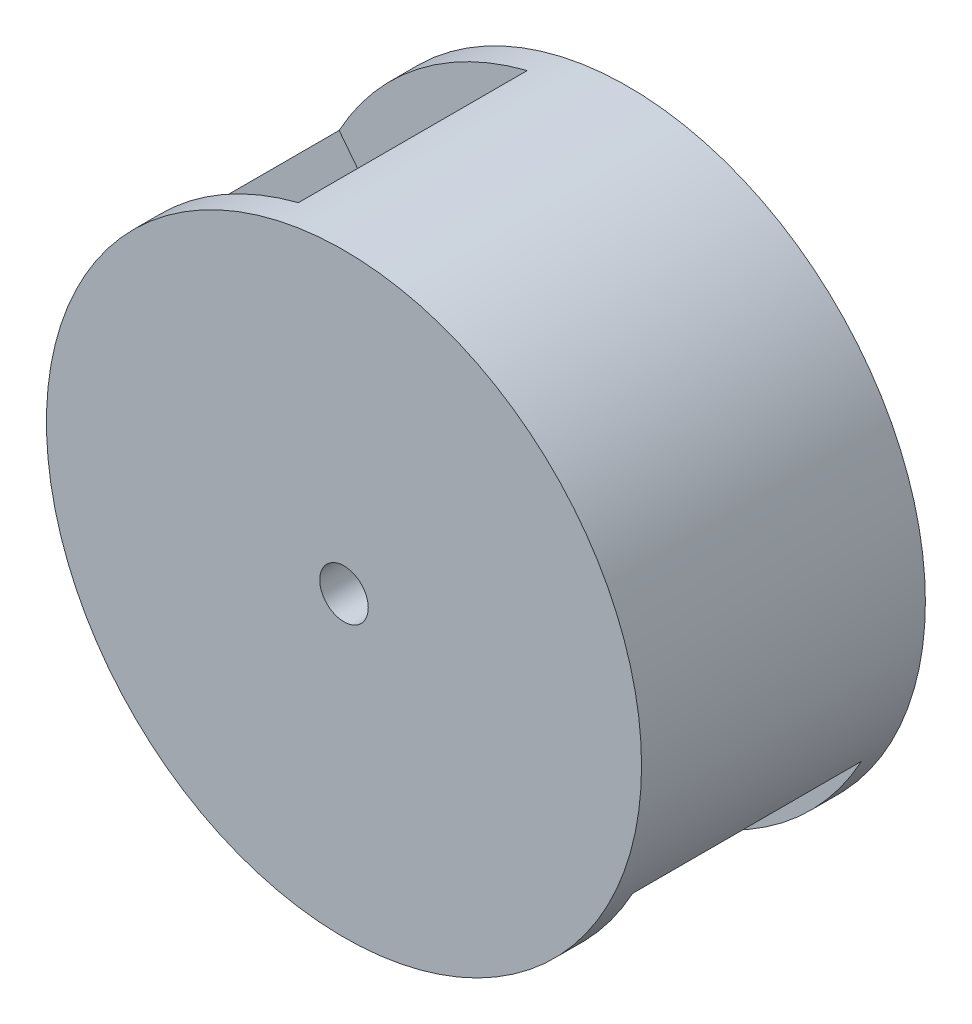
SolidWorks part; units mm, degrees
ref_plane "Front Plane" through (0, 0, 0) normal (0, 0, 1) x (1, 0, 0)
ref_plane "Top Plane" through (0, 0, 0) normal (0, 1, 0) x (1, 0, 0)
ref_plane "Right Plane" through (0, 0, 0) normal (1, 0, 0) x (0, 0, -1)
sketch "Sketch2" plane through (0, 0, 0) normal (0, 0, 1) x (1, 0, 0)
  circle A0 centre (0, 0) radius 32.5
  dimension "D2" = 65
extrude "Boss-Extrude1" add sketch "Sketch2" along normal blind 3
sketch "Sketch3" plane through (0, 0, 3) normal (0, 0, 1) x (1, 0, 0)
  line L0 (0, 7.5) -> (0, 21.2104)
  line L1 (0, -7.5) -> (0, -21.2104)
  line L4 (-20.544, 5.2748) -> (-7.2644, 1.8652)
  line L5 (7.2644, -1.8652) -> (20.544, -5.2748)
  line L6 (-32.5, 0) -> (32.5, 0) construction
  line L7 (-7.2644, 1.8652) -> (7.2644, -1.8652) construction
  line L8 (4.5968, -5.9262) -> (-19.9195, 25.68) construction
  line L9 (-20.544, 5.2748) -> (-28.5285, 15.5684)
  line L10 (0, 21.2104) -> (-7.9845, 31.5039)
  line L11 (0, -21.2104) -> (7.9845, -31.5039)
  line L12 (20.544, -5.2748) -> (28.5285, -15.5684)
  circle A1 centre (0, 0) radius 32.5 construction
  circle A6 centre (0, 0) radius 32.5 construction
  arc A7 (0, 7.5) -> (-7.2644, 1.8652) centre (0, 0) ccw
  arc A8 (-31.479, 8.0824) -> (0, -32.5) centre (0, 0) ccw
  arc A9 (31.479, -8.0824) -> (0, 32.5) centre (0, 0) ccw
  arc A10 (0, -7.5) -> (7.2644, -1.8652) centre (0, 0) ccw
  arc A12 (-31.479, 8.0824) -> (-28.5285, 15.5684) centre (0, 0) cw
  arc A13 (-7.9845, 31.5039) -> (0, 32.5) centre (0, 0) cw
  arc A14 (31.479, -8.0824) -> (28.5285, -15.5684) centre (0, 0) cw
  arc A15 (0, -32.5) -> (7.9845, -31.5039) centre (0, 0) ccw
  dimension "D1" = 15
  dimension "D3" = 14.4
  dimension "D4" = 26
  dimension "D5" = 26
extrude "Boss-Extrude2" add sketch "Sketch3" along normal blind 25
sketch "Sketch4" plane through (0, 0, 28) normal (0, 0, 1) x (1, 0, 0)
  circle A0 centre (0, 0) radius 32.5
  dimension "D1" = 65
extrude "Boss-Extrude3" add sketch "Sketch4" along normal blind 3
sketch "Sketch5" plane through (0, 0, 31) normal (0, 0, 1) x (1, 0, 0)
  line L0 (-1.5492, 2.15) -> (1.5492, 2.15)
  arc A0 (-1.5492, 2.15) -> (1.5492, 2.15) centre (0, 0) ccw
  dimension "D1" = 5.3
  dimension "D2" = 2.15
extrude "Cut-Extrude1" cut sketch "Sketch5" against normal through all
sketch "Sketch7" plane through (0, 0, 31) normal (0, 0, 1) x (1, 0, 0)
  circle A0 centre (0, 0) radius 2.65
  dimension "D1" = 5.3
extrude "Cut-Extrude2" cut sketch "Sketch7" against normal blind 3
sketch "Sketch6" plane through (0, 0, 0) normal (0, 0, 1) x (1, 0, 0)
  line L0 (0, 7.5) -> (0, 32.5)
  line L1 (0, -7.5) -> (0, -32.5)
  line L4 (-31.4759, 8.0943) -> (-7.2637, 1.8679)
  line L5 (7.2637, -1.8679) -> (31.4759, -8.0943)
  line L6 (-32.5, 0) -> (32.5, 0) construction
  line L7 (-7.2637, 1.8679) -> (7.2637, -1.8679) construction
  arc A7 (0, 7.5) -> (-7.2637, 1.8679) centre (0, 0) ccw
  arc A8 (-31.4759, 8.0943) -> (0, -32.5) centre (0, 0) ccw
  arc A9 (31.4759, -8.0943) -> (0, 32.5) centre (0, 0) ccw
  arc A10 (0, -7.5) -> (7.2637, -1.8679) centre (0, 0) ccw
  dimension "D1" = 15
  dimension "D2" = 32.5
  dimension "D3" = 14.422
extrude "Boss-Extrude4" [suppressed] add sketch "Sketch6" along normal blind 23
